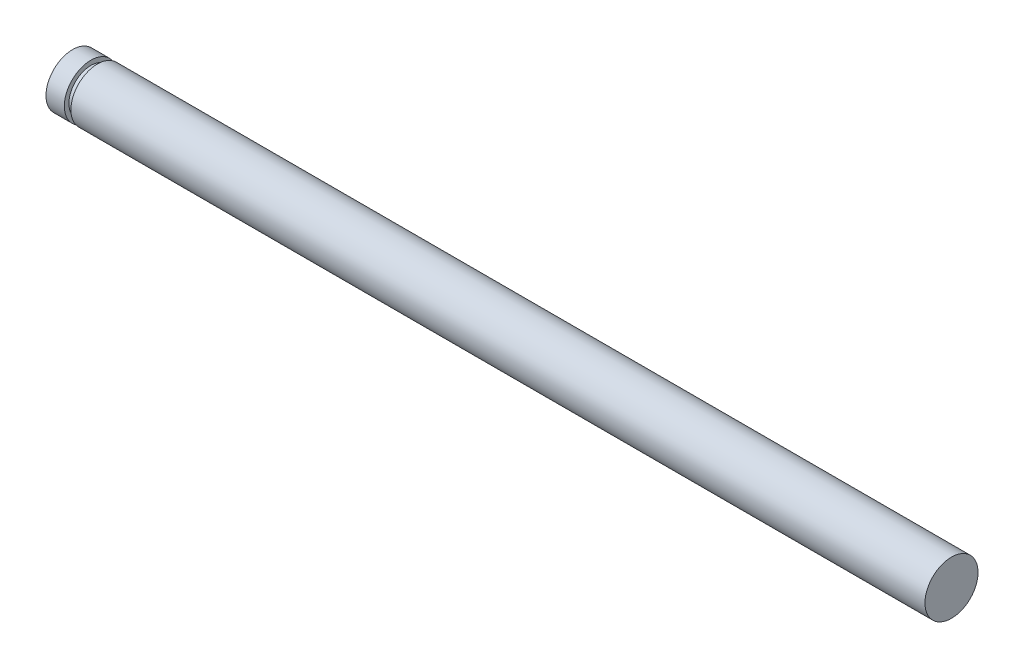
SolidWorks part; units mm, degrees
ref_plane "Front Plane" through (0, 0, 0) normal (0, 0, 1) x (1, 0, 0)
ref_plane "Top Plane" through (0, 0, 0) normal (0, 1, 0) x (1, 0, 0)
ref_plane "Right Plane" through (0, 0, 0) normal (1, 0, 0) x (0, 0, -1)
sketch "Sketch2" plane through (0, 0, 0) normal (0, 0, 1) x (1, 0, 0)
  line L0 (-304.8, 0) -> (304.8, 0) construction
  line L1 (-304.8, 0) -> (-304.8, 18.415)
  line L2 (-304.8, 18.415) -> (-292.1, 18.415)
  line L3 (-292.1, 18.415) -> (-292.1, 15.24)
  line L4 (-292.1, 15.24) -> (-287.528, 15.24)
  line L5 (-287.528, 15.24) -> (-287.528, 18.415)
  line L6 (-287.528, 18.415) -> (304.8, 18.415)
  line L7 (304.8, 18.415) -> (304.8, 0)
  line L8 (-304.8, 0) -> (304.8, 0)
  point P2 (8.636, 18.415)
  dimension "D1" = 609.6
  dimension "D2" = 304.8
  dimension "D3" = 18.415
  dimension "D4" = 12.7
  dimension "D5" = 4.572
  dimension "D6" = 15.24
  dimension "D7" = 18.415
  dimension "D8" = 18.415
revolve "Revolve1" add sketch "Sketch2" angle 360 about L0
